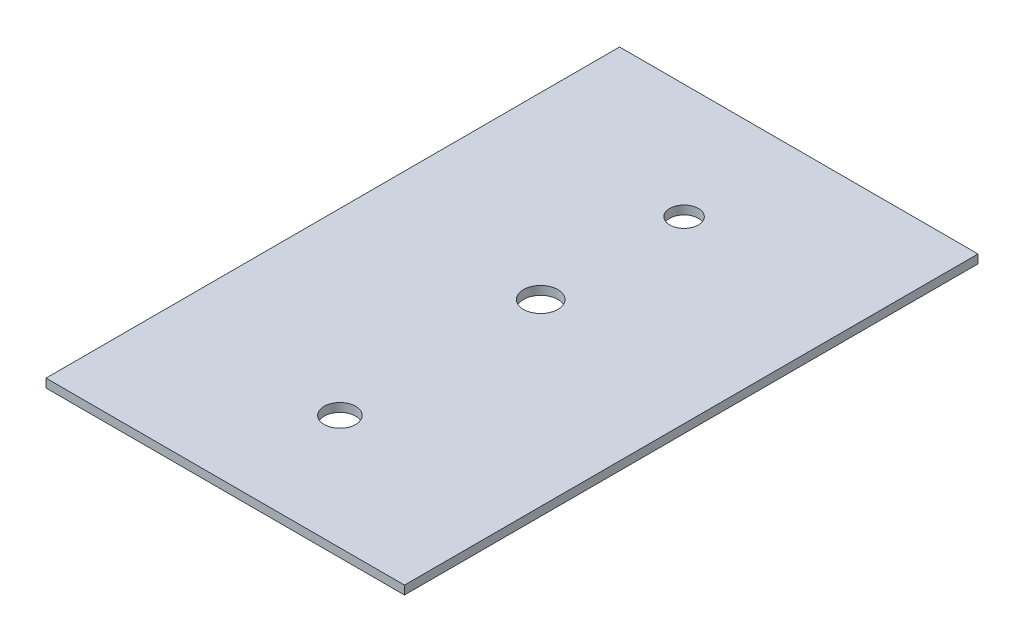
SolidWorks part; units mm, degrees
ref_plane "Front Plane" through (0, 0, 0) normal (0, 0, 1) x (1, 0, 0)
ref_plane "Top Plane" through (0, 0, 0) normal (0, 1, 0) x (1, 0, 0)
ref_plane "Right Plane" through (0, 0, 0) normal (1, 0, 0) x (0, 0, -1)
sketch "Sketch1" plane through (0, 0, 0) normal (0, 1, 0) x (1, 0, 0)
  line L1 (-62.5, -100) -> (62.5, -100)
  line L2 (-62.5, -100) -> (-62.5, 100)
  line L3 (-62.5, 100) -> (62.5, 100)
  line L4 (62.5, -100) -> (62.5, 100)
  line L5 (-62.5, -100) -> (62.5, 100) construction
  line L6 (-62.5, 100) -> (62.5, -100) construction
  point P0 (0, 0)
  dimension "D1" = 125
  dimension "D2" = 200
extrude "Boss-Extrude1" add sketch "Sketch1" along normal blind 3
sketch "Sketch2" plane through (0, 3, 0) normal (0, 1, 0) x (1, 0, 0)
  line L0 (0, 100) -> (0, -100) construction
  line L1 (62.5, 100) -> (-62.5, 100) construction
  line L2 (-62.5, -100) -> (62.5, -100) construction
  circle A0 centre (0, 60) radius 5
  circle A1 centre (0, -60) radius 5.5
  circle A2 centre (0, 10) radius 6
  dimension "D1" = 10
  dimension "D2" = 12
  dimension "D3" = 11
  dimension "D4" = 40
  dimension "D5" = 90
  dimension "D6" = 160
extrude "Cut-Extrude1" cut sketch "Sketch2" along direction (0, -1, 0) on the side against the normal up to next (3 mm away)
